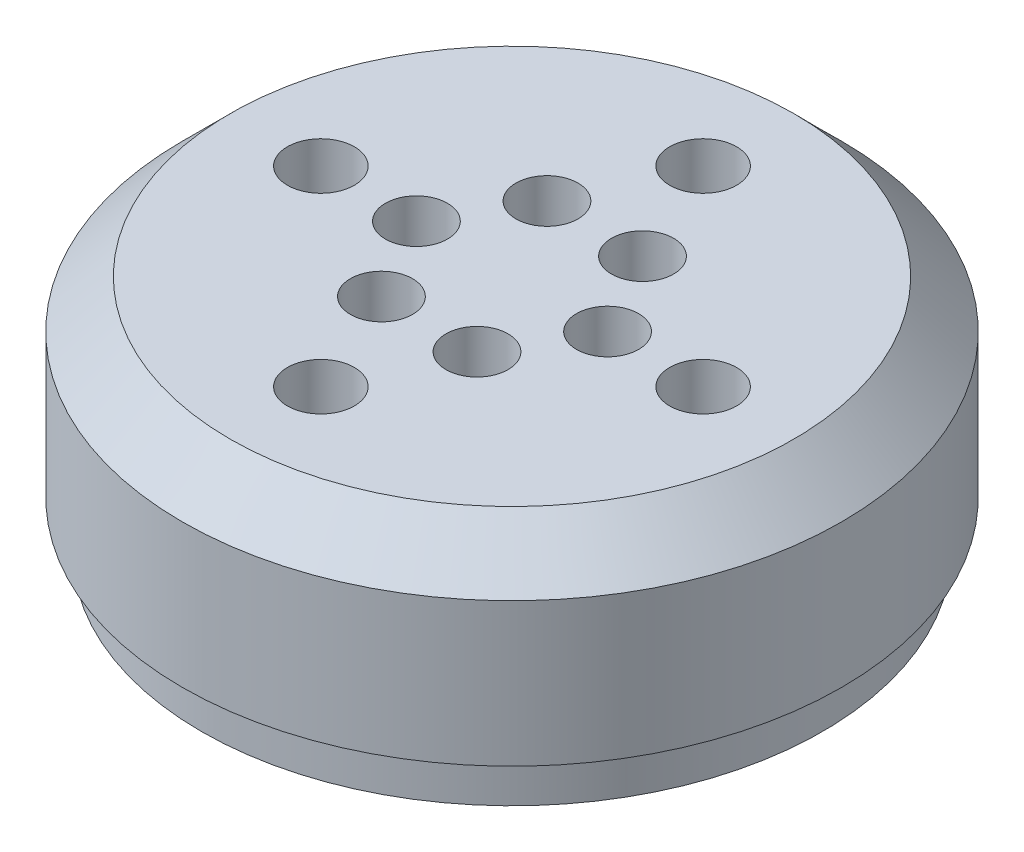
SolidWorks part; units mm, degrees
ref_plane "Front Plane" through (0, 0, 0) normal (0, 0, 1) x (1, 0, 0)
ref_plane "Top Plane" through (0, 0, 0) normal (0, 1, 0) x (1, 0, 0)
ref_plane "Right Plane" through (0, 0, 0) normal (1, 0, 0) x (0, 0, -1)
sketch "Sketch1" plane through (0, 0, 0) normal (0, 1, 0) x (1, 0, 0)
  circle A0 centre (0, 0) radius 32.5
  dimension "D1" = 65
extrude "Boss-Extrude1" add sketch "Sketch1" along normal blind 5
sketch "Sketch2" plane through (0, 0, 0) normal (0, 1, 0) x (1, 0, 0)
  circle A0 centre (0, 0) radius 13.5 construction
  circle A1 centre (-5, 8.6603) radius 1.25
  circle A2 centre (5, 8.6603) radius 1.25
  circle A3 centre (10, 0) radius 1.25
  circle A4 centre (5, -8.6603) radius 1.25
  circle A5 centre (-5, -8.6603) radius 1.25
  circle A6 centre (-10, 0) radius 1.25
  circle A7 centre (0, 0) radius 10 construction
  circle A8 centre (0, 0) radius 4
  point P3 (-10, 0)
  point P4 (-5, 8.6603)
  point P5 (5, 8.6603)
  point P6 (10, 0)
  point P7 (5, -8.6603)
  point P8 (-5, -8.6603)
  point P23 (0, 0)
  dimension "D1" = 27
  dimension "D2" = 2.5
  dimension "D4" = 20
  dimension "D5" = 8
  dimension "D3" = 6
sketch "Sketch3" plane through (0, 5, 0) normal (0, 1, 0) x (1, 0, 0)
  circle A0 centre (0, 0) radius 34.5
  dimension "D1" = 69
extrude "Boss-Extrude3" add sketch "Sketch3" along normal blind 20
extrude "Cut-Extrude1" cut sketch "Sketch2" along normal blind 11.5
sketch "Sketch4" plane through (0, 25, 0) normal (0, 1, 0) x (1, 0, 0)
  circle A0 centre (0, 0) radius 10 construction
  circle A1 centre (10, 0) radius 3.25
  circle A3 centre (5, 8.6603) radius 3.25
  circle A4 centre (5, -8.6603) radius 3.25
  circle A5 centre (-5, -8.6603) radius 3.25
  circle A6 centre (-10, 0) radius 3.25
  circle A7 centre (-5, 8.6603) radius 3.25
  point P15 (0, 0)
  dimension "D1" = 6.5
  dimension "D2" = 6
extrude "Cut-Extrude2" cut sketch "Sketch4" against normal offset from surface (21 mm away) 4 up to face at (5, 0, 9.9103)
sketch "Sketch5" plane through (0, 25, 0) normal (0, 1, 0) x (1, 0, 0)
  line L0 (0, 0) -> (0, 20) construction
  circle A0 centre (0, 0) radius 20 construction
  circle A1 centre (0, 20) radius 3.5
  circle A2 centre (20, 0) radius 3.5
  circle A3 centre (0, -20) radius 3.5
  circle A4 centre (-20, 0) radius 3.5
  point P14 (0, 0)
  dimension "D1" = 40
  dimension "D2" = 7
  dimension "D3" = 4
extrude "Cut-Extrude3" cut sketch "Sketch5" against normal offset from surface (21.5 mm away) 3.5 up to face at (5, 0, 9.9103)
chamfer "Chamfer1" distance 5 angle 45 1 edges at (0, 25, 34.5)
